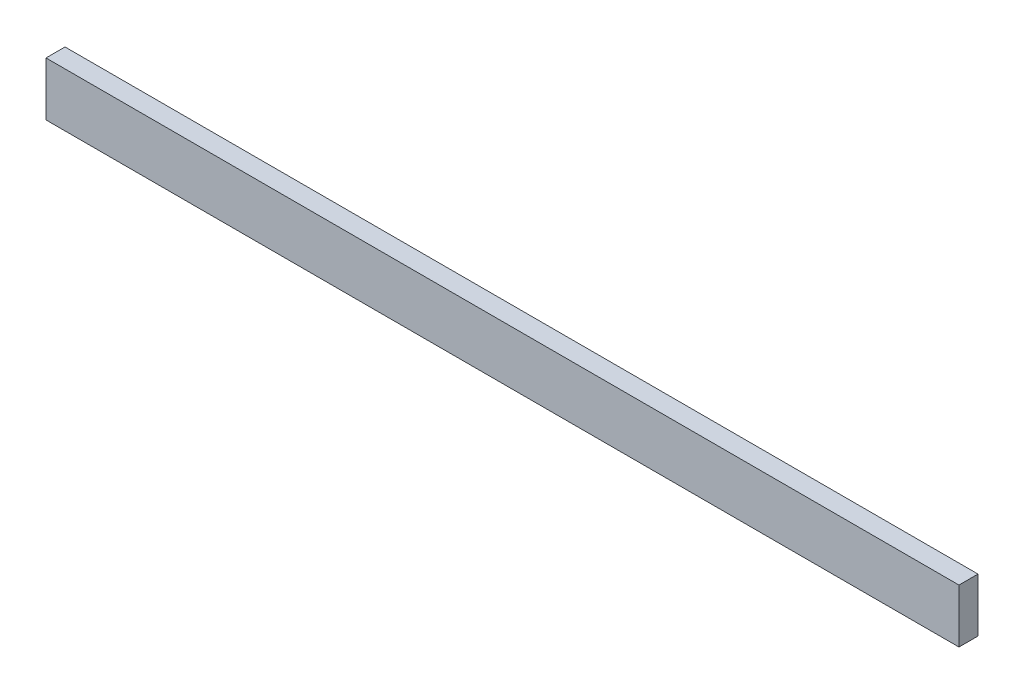
SolidWorks part; units mm, degrees
ref_plane "Alzado" through (0, 0, 0) normal (0, 0, 1) x (1, 0, 0)
ref_plane "Planta" through (0, 0, 0) normal (0, 1, 0) x (1, 0, 0)
ref_plane "Vista lateral" through (0, 0, 0) normal (1, 0, 0) x (0, 0, -1)
sketch "Sketch1" plane through (0, 0, 0) normal (0, 1, 0) x (1, 0, 0)
  line L1 (0, 0) -> (215.9, 0)
  line L2 (0, 0) -> (0, 4.5)
  line L3 (0, 4.5) -> (215.9, 4.5)
  line L4 (215.9, 0) -> (215.9, 4.5)
  dimension "D1" = 215.9
  dimension "D2" = 4.5
extrude "Boss-Extrude1" add sketch "Sketch1" along normal blind 12.7
